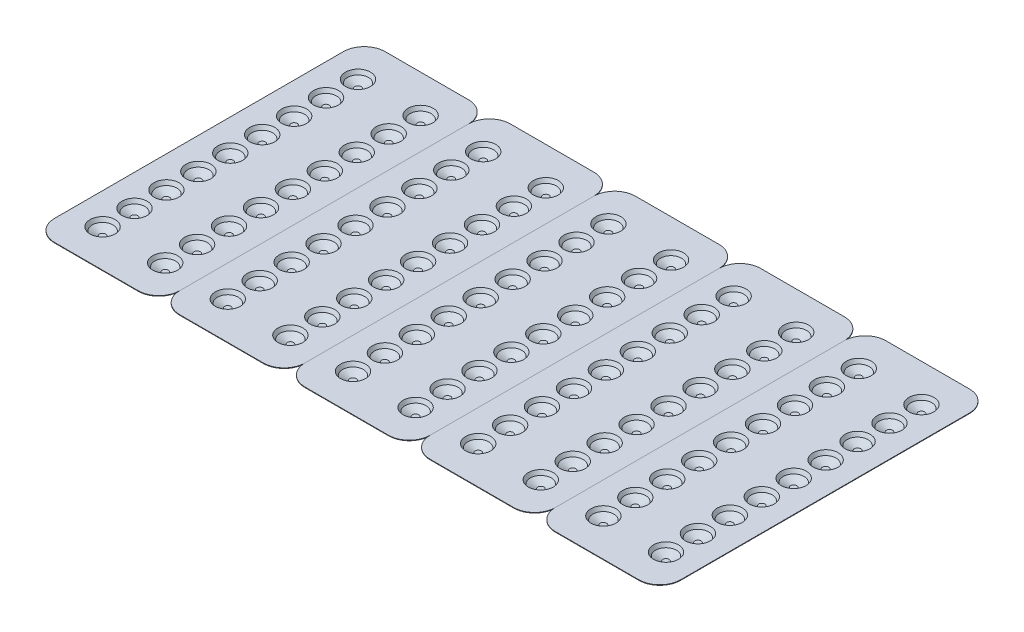
SolidWorks part; units mm, degrees
ref_plane "Płaszczyzna przednia" through (0, 0, 0) normal (0, 0, 1) x (1, 0, 0)
ref_plane "Płaszczyzna górna" through (0, 0, 0) normal (0, 1, 0) x (1, 0, 0)
ref_plane "Płaszczyzna prawa" through (0, 0, 0) normal (1, 0, 0) x (0, 0, -1)
sketch "Szkic1" plane through (0, 0, 0) normal (0, 1, 0) x (1, 0, 0)
  line L1 (-20, 79.2006) -> (20, 79.2006)
  line L2 (-30, 69.2006) -> (-30, -69.2006)
  line L3 (-20, -79.2006) -> (20, -79.2006)
  line L4 (30, 69.2006) -> (30, -69.2006)
  line L5 (-30, 79.2006) -> (30, -79.2006) construction
  line L6 (-30, -79.2006) -> (30, 79.2006) construction
  arc A0 (-20, 79.2006) -> (-30, 69.2006) centre (-20, 69.2006) ccw
  arc A1 (20, 79.2006) -> (30, 69.2006) centre (20, 69.2006) cw
  arc A2 (20, -79.2006) -> (30, -69.2006) centre (20, -69.2006) ccw
  arc A3 (-30, -69.2006) -> (-20, -79.2006) centre (-20, -69.2006) ccw
  point P0 (0, 0)
  dimension "D1" = 10
  dimension "D2" = 158.4012
  dimension "D3" = 60
extrude "Dodanie-wyciągnięcie1" add sketch "Szkic1" along normal blind 0.25
sketch "Szkic2" plane through (0, 0, 0) normal (0, 1, 0) x (1, 0, 0)
  line L0 (-20, -79.2006) -> (20, -79.2006) construction
  line L1 (0, 13.816) -> (0, -29.1646) construction
  circle A0 centre (-15, -61.2006) radius 6
  dimension "D1" = 12
  dimension "D3" = 15
  dimension "D2" = 18
extrude "Wytnij-wyciągnięcie1" cut sketch "Szkic2" along normal through all
ref_plane "Płaszczyzna1" through (-15, 0, 0) normal (1, 0, 0) x (0, 0, -1)
sketch "Szkic3" plane through (-15, 0, 0) normal (1, 0, 0) x (0, 0, -1)
  line L0 (-55.2006, 0.25) -> (-56.1982, -1.4779)
  line L1 (-56.1982, -1.4779) -> (-59.7006, -3.5)
  line L2 (-59.7006, -3.5) -> (-61.2006, -3.5)
  line L3 (-61.2006, -3.5) -> (-61.2006, 0) construction
  line L4 (-61.2006, 0) -> (-34.8921, 0) construction
  line L7 (-61.2006, 0.9003) -> (-61.2006, -6.526) construction
  dimension "D1" = 3.5
  dimension "D2" = 30
  dimension "D3" = 30
  dimension "D4" = 3
revolve "Obrót-cienka ścianka1" add sketch "Szkic3" angle 360 about L7 wall 0.15
pattern_linear "Szyk liniowy4" count 9 spacing 15.3002 along (0, 0, -1) count 2 spacing 30 along (1, 0, 0) of "Obrót-cienka ścianka1", "Wytnij-wyciągnięcie1"
other "CADCloud1" parameters "D1"=0
pattern_linear "Szyk liniowy5" count 5 spacing 60 along (1, 0, 0) of bodies 118
equation "\"D2@Szkic1\"=(\"D1@Szyk liniowy4\"-1)*\"D3@Szyk liniowy4\"+2*\"D2@Szkic2\""
equation "\"D3@Szyk liniowy4\"=\"tracks_pitch\""
equation "\"D1@Szyk liniowy4\"=\"no_of_tracks\""
